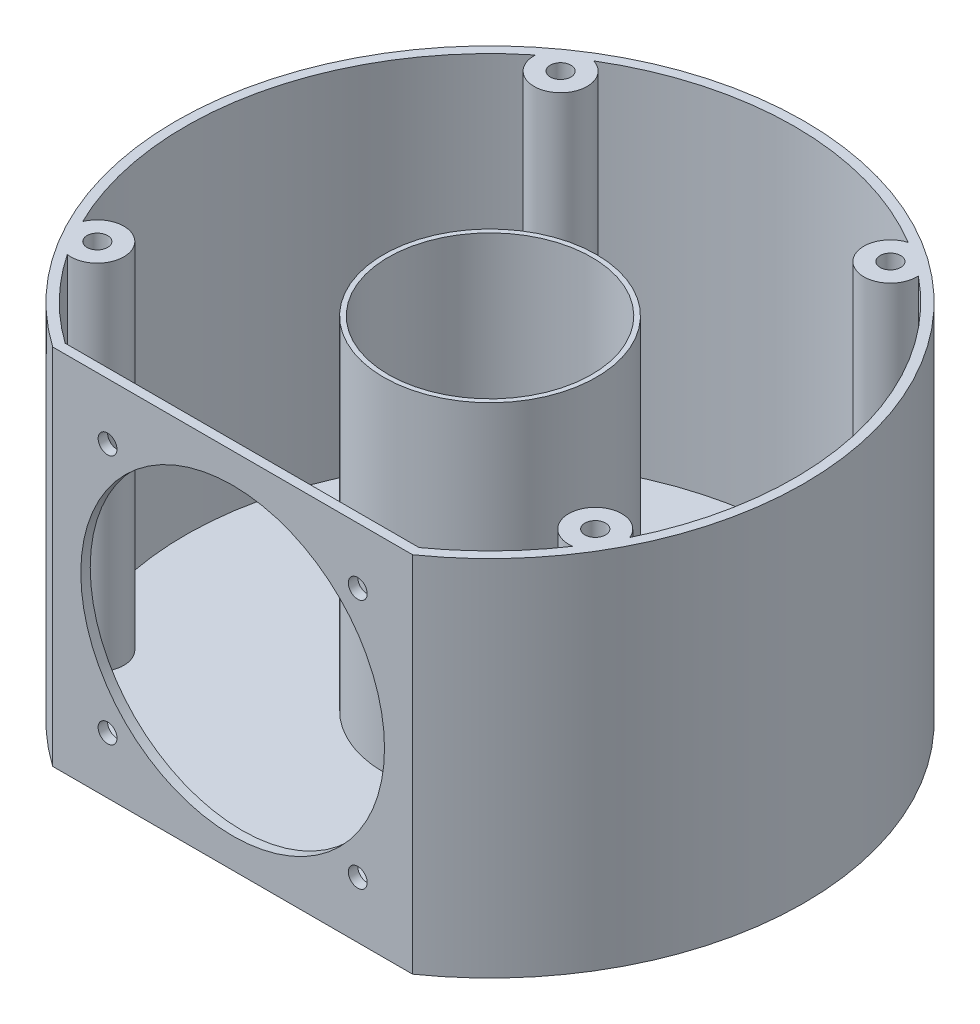
SolidWorks part; units mm, degrees
material "PET"
ref_plane "Front Plane" through (0, 0, 0) normal (0, 0, 1) x (1, 0, 0)
ref_plane "Top Plane" through (0, 0, 0) normal (0, 1, 0) x (1, 0, 0)
ref_plane "Right Plane" through (0, 0, 0) normal (1, 0, 0) x (0, 0, -1)
sketch "Sketch17" plane through (0, 0, 0) normal (0, 1, 0) x (1, 0, 0)
  line L0 (-13.1, -9.1) -> (13.1, -9.1) construction
  line L1 (-13.1, -9.1) -> (13.1, -9.1)
  line L2 (13.1, -9.1) -> (13.1, 10.9) construction
  line L3 (13.1, -9.1) -> (13.1, 10.9)
  line L4 (13.1, 10.9) -> (-13.1, 10.9) construction
  line L5 (13.1, 10.9) -> (-13.1, 10.9)
  line L6 (-13.1, 10.9) -> (-13.1, -9.1) construction
  line L7 (-13.1, 10.9) -> (-13.1, -9.1)
sketch "Base"
  line L0 (-53.2479, 0) -> (53.2479, 0) construction
  line L1 (0, -53.2479) -> (0, 53.2479) construction
  line L2 (-30, -42.0417) -> (30, -42.0417)
  line L3 (0, -18.0417) -> (-48.3942, -18.0417) construction
  line L4 (-30.508, -43.6417) -> (30.508, -43.6417)
  line L5 (0, 0) -> (-13.1, 10.9) construction
  line L6 (-13.1, 10.9) -> (-13.2537, 11.0279) construction
  circle A0 centre (0, 0) radius 17.2417
  arc A1 (30.508, -43.6417) -> (-30.508, -43.6417) centre (0, 0) ccw
  circle A3 centre (0, 0) radius 18.0417
  arc A4 (30, -42.0417) -> (-30, -42.0417) centre (0, 0) ccw
  point P7 (0, 0)
  point P10 (0, 0)
  dimension "D8" = 36.0834
  dimension "D7" = 1.6
  dimension "D4" = 0.8
  dimension "D3" = 24
  dimension "D6" = 1.6
  dimension "D2" = 60
  dimension "D1" = 0.2
extrude "Boss-Extrude4" add sketch "Base" along normal blind 1.6
sketch "Sketch7" plane through (0, 1.6, 0) normal (0, 1, 0) x (1, 0, 0)
  line L0 (-53.2479, 0) -> (53.2479, 0) construction
  line L1 (0, -53.2479) -> (0, 53.2479) construction
  line L2 (-30, -42.0417) -> (30, -42.0417)
  line L3 (0, -18.0417) -> (-48.3942, -18.0417) construction
  line L4 (-30.508, -43.6417) -> (30.508, -43.6417)
  line L5 (0, 0) -> (-13.1, 10.9) construction
  line L6 (-13.1, 10.9) -> (-13.2537, 11.0279) construction
  circle A0 centre (0, 0) radius 17.2417
  arc A1 (30.508, -43.6417) -> (-30.508, -43.6417) centre (0, 0) ccw
  circle A3 centre (0, 0) radius 18.0417
  arc A4 (30, -42.0417) -> (-30, -42.0417) centre (0, 0) ccw
  point P7 (0, 0)
  point P10 (0, 0)
extrude "Boss-Extrude5" add sketch "Sketch7" along normal blind 60
sketch "Horn Face"
  line L4 (-30.508, 61.6) -> (30.508, 0) construction
  line L6 (-30.488, -38.452) -> (-32.0296, -34.6946) construction
  circle A2 centre (0, 30.8) radius 26
  dimension "D1" = 52
sketch "Sketch8" plane through (0, 30.8, 43.6417) normal (0, 0, -1) x (-1, 0, 0)
  line L0 (135.0281, 271.9399) -> (799.6948, 271.9399) construction
  line L1 (22.5, -26) -> (-22.5, -26)
  line L2 (26, -22.5) -> (26, 22.5)
  line L3 (22.5, 26) -> (-22.5, 26)
  line L4 (-26, -22.5) -> (-26, 22.5)
  line L5 (26, -26) -> (-26, 26) construction
  line L6 (26, 26) -> (-26, -26) construction
  line L7 (0, 26) -> (0, -26) construction
  line L8 (-26, 0) -> (26, 0) construction
  circle A0 centre (-21.2132, 21.2132) radius 1.6
  circle A1 centre (21.2132, 21.2132) radius 1.6
  circle A2 centre (-21.2132, -21.2132) radius 1.6
  circle A3 centre (21.2132, -21.2132) radius 1.6
  arc A4 (-22.5, 26) -> (-26, 22.5) centre (-22.5, 22.5) ccw
  arc A5 (26, 22.5) -> (22.5, 26) centre (22.5, 22.5) ccw
  arc A6 (22.5, -26) -> (26, -22.5) centre (22.5, -22.5) ccw
  arc A7 (-22.5, -26) -> (-26, -22.5) centre (-22.5, -22.5) cw
  point P0 (0, 0)
  dimension "D1" = 3.2
extrude "Horn screws" cut sketch "Sketch8" along normal up to next contours A3 | A2 | A0 | A1
sketch "Sketch18" plane through (0, 0, 43.6417) normal (0, 0, 1) x (1, 0, 0)
  circle A0 centre (0, 30.8) radius 25.75
  circle A1 centre (0, 30.8) radius 26 construction
  dimension "D1" = 0.25
extrude "Horn" cut sketch "Sketch18" against normal up to next
sketch "Sketch12" plane through (0, 0, 0) normal (0, -1, 0) x (1, 0, 0)
  circle A0 centre (-42.2169, 24.374) radius 4.5 construction
  circle A1 centre (-42.2169, 24.374) radius 4.5
  circle A2 centre (-42.2169, 24.374) radius 1.75 construction
  circle A3 centre (-42.2169, 24.374) radius 1.75 construction
  circle A4 centre (-27.9606, -39.9319) radius 4.5 construction
  circle A5 centre (-27.9606, -39.9319) radius 4.5
  circle A6 centre (-27.9606, -39.9319) radius 1.75 construction
  circle A7 centre (-27.9606, -39.9319) radius 1.75 construction
  circle A8 centre (27.9606, -39.9319) radius 1.75 construction
  circle A9 centre (27.9606, -39.9319) radius 1.75 construction
  circle A10 centre (27.9606, -39.9319) radius 4.5 construction
  circle A11 centre (27.9606, -39.9319) radius 4.5
  circle A12 centre (42.2169, 24.374) radius 4.5 construction
  circle A13 centre (42.2169, 24.374) radius 4.5
  circle A14 centre (42.2169, 24.374) radius 1.75 construction
  circle A15 centre (42.2169, 24.374) radius 1.75 construction
extrude "PCB screws" add sketch "Sketch12" against normal up to surface (61.6 mm away)
sketch "Sketch21" plane through (0, 0, 0) normal (0, 1, 0) x (1, 0, 0)
  circle A0 centre (-42.2169, -24.374) radius 3.25
  circle A1 centre (42.2169, -24.374) radius 3.25
  circle A2 centre (27.9606, 39.9319) radius 3.25
  circle A3 centre (-27.9606, 39.9319) radius 3.25
  dimension "D1" = 6.5
extrude "Cut-Extrude1" cut sketch "Sketch21" along normal up to next
sketch "Sketch20" plane through (0, 61.6, 0) normal (0, 1, 0) x (1, 0, 0)
  circle A0 centre (-42.2169, -24.374) radius 4.5 construction
  circle A1 centre (-42.2169, -24.374) radius 4.5
  circle A2 centre (42.2169, -24.374) radius 4.5 construction
  circle A3 centre (42.2169, -24.374) radius 4.5
  circle A4 centre (27.9606, 39.9319) radius 4.5 construction
  circle A5 centre (27.9606, 39.9319) radius 4.5
  circle A6 centre (-27.9606, 39.9319) radius 4.5 construction
  circle A7 centre (-27.9606, 39.9319) radius 4.5
  circle A8 centre (-27.9606, 39.9319) radius 1.75 construction
  circle A9 centre (-27.9606, 39.9319) radius 1.75
  circle A10 centre (-42.2169, -24.374) radius 1.75 construction
  circle A11 centre (-42.2169, -24.374) radius 1.75
  circle A12 centre (42.2169, -24.374) radius 1.75 construction
  circle A13 centre (42.2169, -24.374) radius 1.75
  circle A14 centre (27.9606, 39.9319) radius 1.75 construction
  circle A15 centre (27.9606, 39.9319) radius 1.75
extrude "Boss-Extrude6" add sketch "Sketch20" against normal blind 4
sketch "Sketch19" plane through (0, 61.6, 0) normal (0, 1, 0) x (1, 0, 0)
  circle A2 centre (0, 0) radius 18.0417 construction
  circle A3 centre (0, 0) radius 18.0417
extrude "Mast" cut sketch "Sketch19" against normal blind 2
equation "\"wall_thickness\"= 1.6"
equation "\"D1@Boss-Extrude4\"=\"wall_thickness\""
equation "\"D1@Boss-Extrude5\"=\"wall_thickness\""
equation "\"D6@Base\"=\"wall_thickness\""
